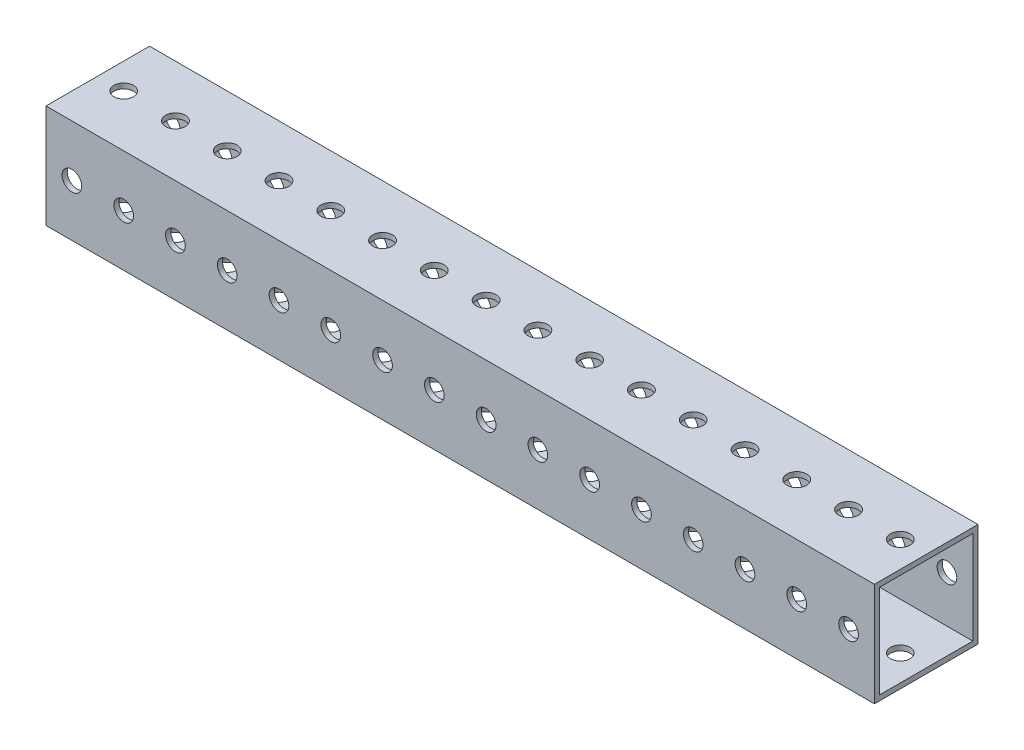
SolidWorks part; units mm, degrees
ref_plane "Front Plane" through (0, 0, 0) normal (0, 0, 1) x (1, 0, 0)
ref_plane "Top Plane" through (0, 0, 0) normal (0, 1, 0) x (1, 0, 0)
ref_plane "Right Plane" through (0, 0, 0) normal (1, 0, 0) x (0, 0, -1)
sketch "Sketch1" plane through (0, 0, 0) normal (0, 1, 0) x (1, 0, 0)
  line L1 (0, 0) -> (203.2, 0)
  line L2 (0, 0) -> (0, 25.4)
  line L3 (0, 25.4) -> (203.2, 25.4)
  line L4 (203.2, 0) -> (203.2, 25.4)
  dimension "D1" = 25.4
  dimension "D2" = 203.2
extrude "Boss-Extrude1" add sketch "Sketch1" along normal blind 25.4
sketch "Sketch2" plane through (0, 0, 0) normal (-1, 0, 0) x (0, 0, 1)
  line L0 (-25.4, 25.4) -> (0, 25.4) construction
  line L1 (-25.4, 0) -> (0, 0) construction
  line L2 (-25.4, 25.4) -> (-25.4, 0) construction
  line L3 (-24.13, 1.27) -> (-1.27, 1.27)
  line L4 (-24.13, 1.27) -> (-24.13, 24.13)
  line L5 (-24.13, 24.13) -> (-1.27, 24.13)
  line L6 (-1.27, 1.27) -> (-1.27, 24.13)
  point P8 (-12.7, 12.7)
  dimension "D1" = 1.27
  dimension "D2" = 1.27
  dimension "D3" = 1.27
extrude "Cut-Extrude1" cut sketch "Sketch2" against normal through all
sketch "Sketch3" plane through (0, 25.4, 0) normal (0, 1, 0) x (1, 0, 0)
  line L0 (203.2, 25.4) -> (0, 25.4) construction
  line L1 (0, 25.4) -> (0, 0) construction
  circle A0 centre (6.35, 12.7) radius 2.413
  circle A1 centre (19.05, 12.7) radius 2.413
  circle A2 centre (31.75, 12.7) radius 2.413
  circle A3 centre (44.45, 12.7) radius 2.413
  circle A4 centre (57.15, 12.7) radius 2.413
  circle A5 centre (69.85, 12.7) radius 2.413
  circle A6 centre (82.55, 12.7) radius 2.413
  circle A7 centre (95.25, 12.7) radius 2.413
  circle A8 centre (107.95, 12.7) radius 2.413
  circle A9 centre (120.65, 12.7) radius 2.413
  circle A10 centre (133.35, 12.7) radius 2.413
  circle A11 centre (146.05, 12.7) radius 2.413
  circle A12 centre (158.75, 12.7) radius 2.413
  circle A13 centre (171.45, 12.7) radius 2.413
  circle A14 centre (184.15, 12.7) radius 2.413
  circle A15 centre (196.85, 12.7) radius 2.413
  dimension "D1" = 12.7
  dimension "D2" = 6.35
  dimension "D3" = 4.826
  dimension "D4" = 14
  dimension "D5" = 3
extrude "Cut-Extrude2" cut sketch "Sketch3" against normal through all
sketch "Sketch4" plane through (0, 0, -25.4) normal (0, 0, -1) x (-1, 0, 0)
  line L0 (-203.2, 0) -> (0, 0) construction
  line L1 (0, 25.4) -> (0, 0) construction
  circle A0 centre (-6.35, 12.7) radius 2.413
  circle A1 centre (-19.05, 12.7) radius 2.413
  circle A2 centre (-31.75, 12.7) radius 2.413
  circle A3 centre (-44.45, 12.7) radius 2.413
  circle A4 centre (-57.15, 12.7) radius 2.413
  circle A5 centre (-69.85, 12.7) radius 2.413
  circle A6 centre (-82.55, 12.7) radius 2.413
  circle A7 centre (-95.25, 12.7) radius 2.413
  circle A8 centre (-107.95, 12.7) radius 2.413
  circle A9 centre (-120.65, 12.7) radius 2.413
  circle A10 centre (-133.35, 12.7) radius 2.413
  circle A11 centre (-146.05, 12.7) radius 2.413
  circle A12 centre (-158.75, 12.7) radius 2.413
  circle A13 centre (-171.45, 12.7) radius 2.413
  circle A14 centre (-184.15, 12.7) radius 2.413
  circle A15 centre (-196.85, 12.7) radius 2.413
  dimension "D1" = 4.826
  dimension "D2" = 12.7
  dimension "D3" = 6.35
  dimension "D4" = 14
  dimension "D5" = 3
extrude "Cut-Extrude3" cut sketch "Sketch4" against normal through all
